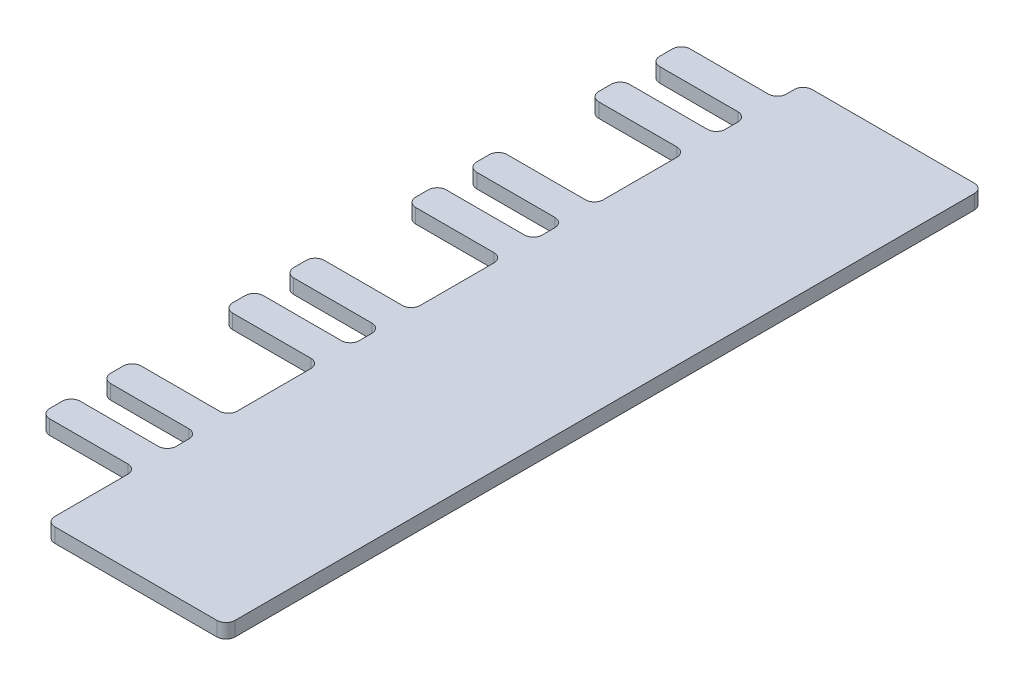
SolidWorks part; units mm, degrees
ref_plane "Front Plane" through (0, 0, 0) normal (0, 0, 1) x (1, 0, 0)
ref_plane "Top Plane" through (0, 0, 0) normal (0, 1, 0) x (1, 0, 0)
ref_plane "Right Plane" through (0, 0, 0) normal (1, 0, 0) x (0, 0, -1)
sketch "Sketch1" plane through (0, 0, 0) normal (0, 1, 0) x (1, 0, 0)
  line L0 (-0.75, 7.5725) -> (-7.25, 7.5725)
  line L2 (0, 6.8225) -> (0, 0.75)
  line L5 (-8, 8.8425) -> (5.7163, 8.8425) construction
  line L7 (-8, 8.3225) -> (-8, 9.3625)
  line L8 (-7.25, 10.1125) -> (-0.7462, 10.1125)
  line L12 (0, 11.9025) -> (0, 10.7874)
  line L17 (-0.75, 12.6525) -> (-7.25, 12.6525)
  line L22 (-8, 13.4025) -> (-8, 14.4425)
  line L27 (-7.25, 15.1925) -> (-0.7462, 15.1925)
  line L56 (14.25, 0) -> (0.75, 0)
  line L84 (0, 16.9825) -> (0, 10.91) [skipped]
  line L85 (-0.75, 17.7325) -> (-7.25, 17.7325) [skipped]
  line L86 (-8, 18.4825) -> (-8, 19.5225) [skipped]
  line L87 (-7.25, 20.2725) -> (-0.7462, 20.2725) [skipped]
  line L88 (0, 22.0625) -> (0, 15.99) [skipped]
  line L89 (-0.75, 22.8125) -> (-7.25, 22.8125) [skipped]
  line L90 (-8, 23.5625) -> (-8, 24.6025) [skipped]
  line L91 (-7.25, 25.3525) -> (-0.7462, 25.3525) [skipped]
  line L92 (0, 27.1425) -> (0, 21.07) [skipped]
  line L93 (-0.75, 27.8925) -> (-7.25, 27.8925) [skipped]
  line L94 (-8, 28.6425) -> (-8, 29.6825) [skipped]
  line L95 (-7.25, 30.4325) -> (-0.7462, 30.4325) [skipped]
  line L96 (0, 32.2225) -> (0, 26.15) [skipped]
  line L97 (-0.75, 32.9725) -> (-7.25, 32.9725) [skipped]
  line L98 (-8, 33.7225) -> (-8, 34.7625) [skipped]
  line L99 (-7.25, 35.5125) -> (-0.7462, 35.5125) [skipped]
  line L100 (0, 37.3025) -> (0, 31.23) [skipped]
  line L101 (-0.75, 38.0525) -> (-7.25, 38.0525) [skipped]
  line L102 (-8, 38.8025) -> (-8, 39.8425) [skipped]
  line L103 (-7.25, 40.5925) -> (-0.7462, 40.5925) [skipped]
  line L104 (0, 42.3825) -> (0, 36.31) [skipped]
  line L105 (-0.75, 43.1325) -> (-7.25, 43.1325) [skipped]
  line L106 (-8, 43.8825) -> (-8, 44.9225) [skipped]
  line L107 (-7.25, 45.6725) -> (-0.7462, 45.6725) [skipped]
  line L108 (0, 47.4625) -> (0, 41.39) [skipped]
  line L109 (-0.75, 48.2125) -> (-7.25, 48.2125) [skipped]
  line L110 (-8, 48.9625) -> (-8, 50.0025) [skipped]
  line L111 (-7.25, 50.7525) -> (-0.7462, 50.7525) [skipped]
  line L112 (0, 52.5425) -> (0, 46.47) [skipped]
  line L113 (-0.75, 53.2925) -> (-7.25, 53.2925) [skipped]
  line L114 (-8, 54.0425) -> (-8, 55.0825) [skipped]
  line L115 (-7.25, 55.8325) -> (-0.7462, 55.8325) [skipped]
  line L116 (-0.75, 22.8125) -> (-7.25, 22.8125)
  line L117 (-8, 23.5625) -> (-8, 24.6025)
  line L118 (-7.25, 25.3525) -> (-0.7462, 25.3525)
  line L119 (0, 27.1425) -> (0, 26.0274)
  line L120 (-0.75, 27.8925) -> (-7.25, 27.8925)
  line L121 (-8, 28.6425) -> (-8, 29.6825)
  line L122 (-7.25, 30.4325) -> (-0.7462, 30.4325)
  line L123 (-0.75, 38.0525) -> (-7.25, 38.0525)
  line L124 (-8, 38.8025) -> (-8, 39.8425)
  line L125 (-7.25, 40.5925) -> (-0.7462, 40.5925)
  line L126 (0, 42.3825) -> (0, 41.2674)
  line L127 (-0.75, 43.1325) -> (-7.25, 43.1325)
  line L128 (-8, 43.8825) -> (-8, 44.9225)
  line L129 (-7.25, 45.6725) -> (-0.7462, 45.6725)
  line L130 (-0.75, 53.2925) -> (-7.25, 53.2925)
  line L131 (-8, 54.0425) -> (-8, 55.0825)
  line L132 (-7.25, 55.8325) -> (-0.7462, 55.8325)
  line L133 (0, 57.6225) -> (0, 56.5074)
  line L134 (-0.75, 58.3725) -> (-7.25, 58.3725)
  line L135 (-8, 59.1225) -> (-8, 60.1625)
  line L136 (-7.25, 60.9125) -> (-0.7462, 60.9125)
  line L137 (0, 22.0625) -> (0, 15.8674)
  line L138 (0, 31.1074) -> (0, 37.3025)
  line L139 (0, 46.3474) -> (0, 52.5425)
  line L140 (0, 61.5874) -> (0, 62.3125)
  line L141 (0.75, 63.0625) -> (14.25, 63.0625)
  line L142 (15, 62.3125) -> (15, 0.75)
  arc A0 (-0.7462, 10.1125) -> (0, 10.7874) centre (-0.7462, 10.8625) ccw
  arc A1 (-8, 9.3625) -> (-7.25, 10.1125) centre (-7.25, 9.3625) cw
  arc A2 (-7.25, 7.5725) -> (-8, 8.3225) centre (-7.25, 8.3225) cw
  arc A3 (0, 0.75) -> (0.75, 0) centre (0.75, 0.75) ccw
  arc A4 (-0.75, 7.5725) -> (0, 6.8225) centre (-0.75, 6.8225) cw
  arc A5 (15, 0.75) -> (14.25, 0) centre (14.25, 0.75) cw
  arc A6 (-0.75, 12.6525) -> (0, 11.9025) centre (-0.75, 11.9025) cw
  arc A7 (-7.25, 12.6525) -> (-8, 13.4025) centre (-7.25, 13.4025) cw
  arc A8 (-8, 14.4425) -> (-7.25, 15.1925) centre (-7.25, 14.4425) cw
  arc A9 (-0.7462, 15.1925) -> (0, 15.8674) centre (-0.7462, 15.9425) ccw
  arc A44 (-0.75, 17.7325) -> (0, 16.9825) centre (-0.75, 16.9825) cw [skipped]
  arc A45 (-7.25, 17.7325) -> (-8, 18.4825) centre (-7.25, 18.4825) cw [skipped]
  arc A46 (-8, 19.5225) -> (-7.25, 20.2725) centre (-7.25, 19.5225) cw [skipped]
  arc A47 (-0.7462, 20.2725) -> (0, 20.9474) centre (-0.7462, 21.0225) ccw [skipped]
  arc A48 (-0.75, 22.8125) -> (0, 22.0625) centre (-0.75, 22.0625) cw [skipped]
  arc A49 (-7.25, 22.8125) -> (-8, 23.5625) centre (-7.25, 23.5625) cw [skipped]
  arc A50 (-8, 24.6025) -> (-7.25, 25.3525) centre (-7.25, 24.6025) cw [skipped]
  arc A51 (-0.7462, 25.3525) -> (0, 26.0274) centre (-0.7462, 26.1025) ccw [skipped]
  arc A52 (-0.75, 27.8925) -> (0, 27.1425) centre (-0.75, 27.1425) cw [skipped]
  arc A53 (-7.25, 27.8925) -> (-8, 28.6425) centre (-7.25, 28.6425) cw [skipped]
  arc A54 (-8, 29.6825) -> (-7.25, 30.4325) centre (-7.25, 29.6825) cw [skipped]
  arc A55 (-0.7462, 30.4325) -> (0, 31.1074) centre (-0.7462, 31.1825) ccw [skipped]
  arc A56 (-0.75, 32.9725) -> (0, 32.2225) centre (-0.75, 32.2225) cw [skipped]
  arc A57 (-7.25, 32.9725) -> (-8, 33.7225) centre (-7.25, 33.7225) cw [skipped]
  arc A58 (-8, 34.7625) -> (-7.25, 35.5125) centre (-7.25, 34.7625) cw [skipped]
  arc A59 (-0.7462, 35.5125) -> (0, 36.1874) centre (-0.7462, 36.2625) ccw [skipped]
  arc A60 (-0.75, 38.0525) -> (0, 37.3025) centre (-0.75, 37.3025) cw [skipped]
  arc A61 (-7.25, 38.0525) -> (-8, 38.8025) centre (-7.25, 38.8025) cw [skipped]
  arc A62 (-8, 39.8425) -> (-7.25, 40.5925) centre (-7.25, 39.8425) cw [skipped]
  arc A63 (-0.7462, 40.5925) -> (0, 41.2674) centre (-0.7462, 41.3425) ccw [skipped]
  arc A64 (-0.75, 43.1325) -> (0, 42.3825) centre (-0.75, 42.3825) cw [skipped]
  arc A65 (-7.25, 43.1325) -> (-8, 43.8825) centre (-7.25, 43.8825) cw [skipped]
  arc A66 (-8, 44.9225) -> (-7.25, 45.6725) centre (-7.25, 44.9225) cw [skipped]
  arc A67 (-0.7462, 45.6725) -> (0, 46.3474) centre (-0.7462, 46.4225) ccw [skipped]
  arc A68 (-0.75, 48.2125) -> (0, 47.4625) centre (-0.75, 47.4625) cw [skipped]
  arc A69 (-7.25, 48.2125) -> (-8, 48.9625) centre (-7.25, 48.9625) cw [skipped]
  arc A70 (-8, 50.0025) -> (-7.25, 50.7525) centre (-7.25, 50.0025) cw [skipped]
  arc A71 (-0.7462, 50.7525) -> (0, 51.4274) centre (-0.7462, 51.5025) ccw [skipped]
  arc A72 (-0.75, 53.2925) -> (0, 52.5425) centre (-0.75, 52.5425) cw [skipped]
  arc A73 (-7.25, 53.2925) -> (-8, 54.0425) centre (-7.25, 54.0425) cw [skipped]
  arc A74 (-8, 55.0825) -> (-7.25, 55.8325) centre (-7.25, 55.0825) cw [skipped]
  arc A75 (-0.7462, 55.8325) -> (0, 56.5074) centre (-0.7462, 56.5825) ccw [skipped]
  arc A76 (-0.7462, 25.3525) -> (0, 26.0274) centre (-0.7462, 26.1025) ccw
  arc A77 (-8, 24.6025) -> (-7.25, 25.3525) centre (-7.25, 24.6025) cw
  arc A78 (-7.25, 22.8125) -> (-8, 23.5625) centre (-7.25, 23.5625) cw
  arc A79 (-0.75, 22.8125) -> (0, 22.0625) centre (-0.75, 22.0625) cw
  arc A80 (-0.75, 27.8925) -> (0, 27.1425) centre (-0.75, 27.1425) cw
  arc A81 (-7.25, 27.8925) -> (-8, 28.6425) centre (-7.25, 28.6425) cw
  arc A82 (-8, 29.6825) -> (-7.25, 30.4325) centre (-7.25, 29.6825) cw
  arc A83 (-0.7462, 30.4325) -> (0, 31.1074) centre (-0.7462, 31.1825) ccw
  arc A84 (-0.7462, 40.5925) -> (0, 41.2674) centre (-0.7462, 41.3425) ccw
  arc A85 (-8, 39.8425) -> (-7.25, 40.5925) centre (-7.25, 39.8425) cw
  arc A86 (-7.25, 38.0525) -> (-8, 38.8025) centre (-7.25, 38.8025) cw
  arc A87 (-0.75, 38.0525) -> (0, 37.3025) centre (-0.75, 37.3025) cw
  arc A88 (-0.75, 43.1325) -> (0, 42.3825) centre (-0.75, 42.3825) cw
  arc A89 (-7.25, 43.1325) -> (-8, 43.8825) centre (-7.25, 43.8825) cw
  arc A90 (-8, 44.9225) -> (-7.25, 45.6725) centre (-7.25, 44.9225) cw
  arc A91 (-0.7462, 45.6725) -> (0, 46.3474) centre (-0.7462, 46.4225) ccw
  arc A92 (-0.7462, 55.8325) -> (0, 56.5074) centre (-0.7462, 56.5825) ccw
  arc A93 (-8, 55.0825) -> (-7.25, 55.8325) centre (-7.25, 55.0825) cw
  arc A94 (-7.25, 53.2925) -> (-8, 54.0425) centre (-7.25, 54.0425) cw
  arc A95 (-0.75, 53.2925) -> (0, 52.5425) centre (-0.75, 52.5425) cw
  arc A96 (-0.75, 58.3725) -> (0, 57.6225) centre (-0.75, 57.6225) cw
  arc A97 (-7.25, 58.3725) -> (-8, 59.1225) centre (-7.25, 59.1225) cw
  arc A98 (-8, 60.1625) -> (-7.25, 60.9125) centre (-7.25, 60.1625) cw
  arc A99 (-0.7462, 60.9125) -> (0, 61.5874) centre (-0.7462, 61.6625) ccw
  arc A100 (0, 62.3125) -> (0.75, 63.0625) centre (0.75, 62.3125) cw
  arc A101 (14.25, 63.0625) -> (15, 62.3125) centre (14.25, 62.3125) cw
  point P0 (0, 0)
  point P27 (0, 10.1125)
  point P46 (0, 25.3525)
  point P48 (-8, 10.1125)
  point P69 (-8, 7.5725)
  point P73 (0, 40.5925)
  point P78 (0, 0)
  point P81 (0, 7.5725)
  point P84 (15, 0)
  point P108 (0, 55.8325)
  point P123 (-3.9981, 60.9125)
  dimension "D6" = 0.75
  dimension "D7" = 0.75
  dimension "D8" = 4
  dimension "D9" = 10.16
  dimension "D11" = 0.75
  dimension "D1" = 2.54
  dimension "D2" = 8
  dimension "D3" = 10
  dimension "D4" = 7.5725
  dimension "D5" = 15
  dimension "D10" = 5.08
  dimension "D12" = 2.15
extrude "Boss-Extrude1" add sketch "Sketch1" along normal blind 1.2
